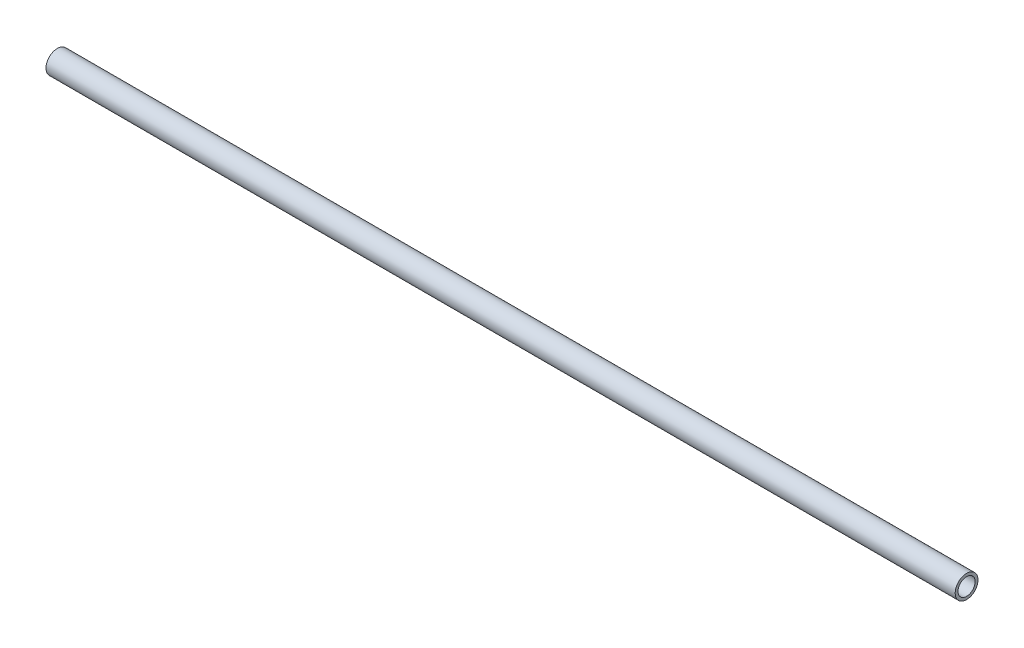
SolidWorks part; units mm, degrees
material "Hexcel AS4C (3000 Filaments)"
ref_plane "Front Plane" through (0, 0, 0) normal (0, 0, 1) x (1, 0, 0)
ref_plane "Top Plane" through (0, 0, 0) normal (0, 1, 0) x (1, 0, 0)
ref_plane "Right Plane" through (0, 0, 0) normal (1, 0, 0) x (0, 0, -1)
sketch "Sketch2" plane through (0, 0, 0) normal (1, 0, 0) x (0, 0, -1)
  circle A0 centre (0, 0) radius 8
  circle A1 centre (0, 0) radius 6
extrude "Boss-Extrude1" add sketch "Sketch2" along normal blind 638
